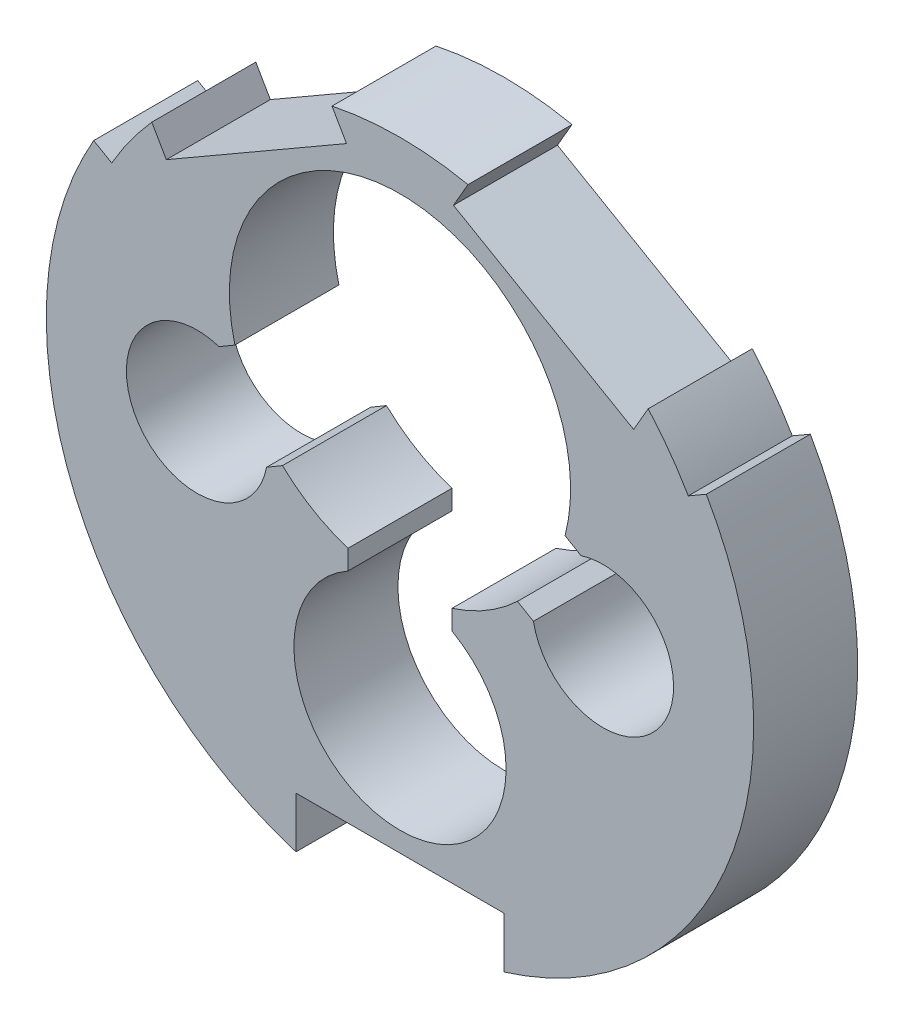
SolidWorks part; units mm, degrees
ref_plane "Спереди" through (0, 0, 0) normal (0, 0, 1) x (1, 0, 0)
ref_plane "Сверху" through (0, 0, 0) normal (0, 1, 0) x (1, 0, 0)
ref_plane "Справа" through (0, 0, 0) normal (1, 0, 0) x (0, 0, -1)
sketch "Эскиз1" plane through (0, 0, 0) normal (0, 0, 1) x (1, 0, 0)
  line L0 (0, 0) -> (-8, 13.8564) construction
  line L1 (0, 16) -> (0, -16) construction
  line L2 (3.2692, 15.6624) -> (2.5699, 14.4512)
  line L3 (2.5699, 14.4512) -> (11.2301, 9.4512)
  line L4 (11.2301, 9.4512) -> (11.9295, 10.6624)
  line L5 (0, -13.8) -> (-5, -13.8)
  line L6 (-5, -13.8) -> (-5, -15.1987)
  line L7 (0, -13.8) -> (5, -13.8)
  line L8 (5, -13.8) -> (5, -15.1987)
  line L9 (-11.9295, 10.6624) -> (-11.2301, 9.4512)
  line L10 (-11.2301, 9.4512) -> (-2.5699, 14.4512)
  line L11 (-2.5699, 14.4512) -> (-3.2692, 15.6624)
  line L12 (-2.5, -2.3596) -> (-2.5, -3.3048)
  line L13 (2.5, -2.3596) -> (2.5, -3.3048)
  line L14 (-9.75, -0.3) -> (0, 5.45) construction
  line L15 (-8.6973, 2.9329) -> (-7.9351, 3.3825)
  line L16 (-6.4114, -0.9432) -> (-5.6491, -0.4937)
  line L17 (6.4114, -0.9432) -> (5.6491, -0.4937)
  line L18 (8.6973, 2.9329) -> (7.9351, 3.3825)
  arc A0 (7.9351, 3.3825) -> (-7.9351, 3.3825) centre (0, 5.45) ccw
  arc A1 (-5.6491, -0.4937) -> (-2.5, -2.3596) centre (0, 5.45) ccw
  arc A2 (-2.5, -3.3048) -> (2.5, -3.3048) centre (0, -7.75) ccw
  arc A3 (-8.6973, 2.9329) -> (-6.4114, -0.9432) centre (-9.75, -0.3) ccw
  arc A4 (8.6973, 2.9329) -> (6.4114, -0.9432) centre (9.75, -0.3) cw
  arc A5 (2.5, -2.3596) -> (5.6491, -0.4937) centre (0, 5.45) ccw
  arc A6 (3.2692, 15.6624) -> (-3.2692, 15.6624) centre (0, 0) ccw
  arc A7 (5, -15.1987) -> (11.9295, 10.6624) centre (0, 0) ccw
  arc A8 (-11.9295, 10.6624) -> (-5, -15.1987) centre (0, 0) ccw
  point P5 (0, 0)
  dimension "D1" = 16
  dimension "D2" = 10.2
  dimension "D3" = 13.8
  dimension "D4" = 30
  dimension "D5" = 6.8
  dimension "D9" = 16.4
  dimension "D14" = 4.5
  dimension "D15" = 7.45
  dimension "D6" = 10
  dimension "D7" = 7.75
  dimension "D8" = 5.45
  dimension "D10" = 13.8
  dimension "D11" = 10
  dimension "D12" = 19.5
  dimension "D13" = 5
extrude "Бобышка-Вытянуть1" add sketch "Эскиз1" along normal mid plane 5
sketch "Sketch2" plane through (0, 0, 0) normal (0, 0, 1) x (1, 0, 0)
  line L0 (-16.9337, 1.5) -> (16.9337, 1.5) construction
  line L1 (-13.8564, 8) -> (-14.7224, 8.5)
  line L2 (13.8564, 8) -> (14.7224, 8.5)
  line L3 (-5, -15.1987) -> (-5, -16.2481)
  line L4 (5, -15.1987) -> (5, -16.2481)
  line L5 (0, 0) -> (0, 27.3636) construction
  line L6 (0, 0) -> (-2.5981, 1.5)
  line L7 (0, 0) -> (2.5981, 1.5)
  arc A0 (-13.8564, 8) -> (-5, -15.1987) centre (0, 0) ccw
  arc A2 (-14.7224, 8.5) -> (-5, -16.2481) centre (0, 0) ccw
  arc A3 (5, -15.1987) -> (13.8564, 8) centre (0, 0) ccw
  arc A4 (5, -16.2481) -> (14.7224, 8.5) centre (0, 0) ccw
  dimension "D1" = 17
  dimension "D2" = 1.5
  dimension "D3" = 60
  dimension "D4" = 60
extrude "Boss-Extrude3" add sketch "Sketch2" along normal up to surface and the other way up to surface
sketch "Sketch3" plane through (0, 0, 0) normal (0, 0, 1) x (1, 0, 0)
  line L11 (-3.2692, 15.6624) -> (-2.5699, 14.4512)
  line L12 (-2.5699, 14.4512) -> (-11.2301, 9.4512)
  line L13 (-11.2301, 9.4512) -> (-11.9295, 10.6624)
  line L14 (-13.8564, 8) -> (-14.7224, 8.5)
  line L15 (-5, -16.2481) -> (-5, -13.8)
  line L16 (-5, -13.8) -> (5, -13.8)
  line L17 (5, -13.8) -> (5, -16.2481)
  line L18 (14.7224, 8.5) -> (13.8564, 8)
  line L19 (11.9295, 10.6624) -> (11.2301, 9.4512)
  line L20 (11.2301, 9.4512) -> (2.5699, 14.4512)
  line L21 (2.5699, 14.4512) -> (3.2692, 15.6624)
  line L22 (-3.2692, 15.6624) -> (-2.5699, 14.4512)
  line L23 (-2.5699, 14.4512) -> (-11.2301, 9.4512)
  line L24 (-11.2301, 9.4512) -> (-11.9295, 10.6624)
  line L25 (-13.8564, 8) -> (-14.7224, 8.5)
  line L26 (-5, -16.2481) -> (-5, -13.8)
  line L27 (-5, -13.8) -> (5, -13.8)
  line L28 (5, -13.8) -> (5, -16.2481)
  line L29 (14.7224, 8.5) -> (13.8564, 8)
  line L30 (11.9295, 10.6624) -> (11.2301, 9.4512)
  line L31 (11.2301, 9.4512) -> (2.5699, 14.4512)
  line L32 (2.5699, 14.4512) -> (3.2692, 15.6624)
  arc A5 (3.2692, 15.6624) -> (-3.2692, 15.6624) centre (0, 0) ccw
  arc A6 (-11.9295, 10.6624) -> (-13.8564, 8) centre (0, 0) ccw
  arc A7 (-14.7224, 8.5) -> (-5, -16.2481) centre (0, 0) ccw
  arc A8 (5, -16.2481) -> (14.7224, 8.5) centre (0, 0) ccw
  arc A9 (13.8564, 8) -> (11.9295, 10.6624) centre (0, 0) ccw
  arc A10 (3.2692, 15.6624) -> (-3.2692, 15.6624) centre (0, 0) ccw
  arc A11 (-11.9295, 10.6624) -> (-13.8564, 8) centre (0, 0) ccw
  arc A12 (-14.7224, 8.5) -> (-5, -16.2481) centre (0, 0) ccw
  arc A13 (5, -16.2481) -> (14.7224, 8.5) centre (0, 0) ccw
  arc A14 (13.8564, 8) -> (11.9295, 10.6624) centre (0, 0) ccw
  dimension "D1" = 0
